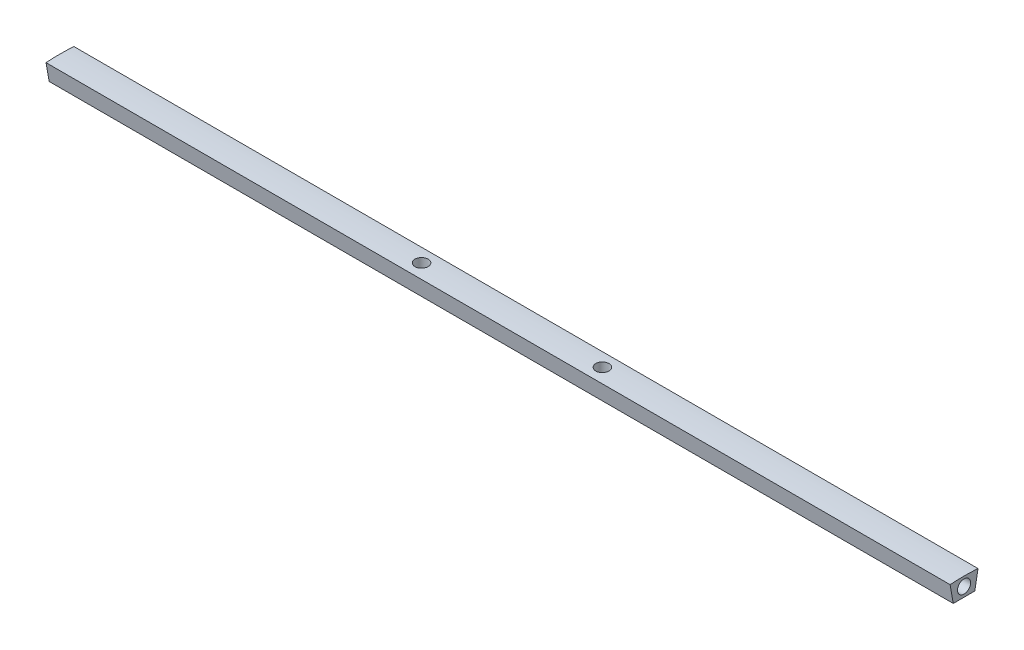
SolidWorks part; units mm, degrees
ref_plane "Спереди" through (0, 0, 0) normal (0, 0, 1) x (1, 0, 0)
ref_plane "Сверху" through (0, 0, 0) normal (0, 1, 0) x (1, 0, 0)
ref_plane "Справа" through (0, 0, 0) normal (1, 0, 0) x (0, 0, -1)
sketch "Эскиз1" plane through (0, 0, 0) normal (1, 0, 0) x (0, 0, -1)
  line L0 (-3.0855, 17.4987) -> (-2.3866, 13.535)
  line L1 (0, -1000) -> (0, 49000) construction
  line L2 (2.3866, 13.535) -> (3.0855, 17.4987)
  line L3 (-2.3866, 13.535) -> (2.3866, 13.535)
  arc A0 (-35.7, 0) -> (35.7, 0) centre (0, -27.3954) cw construction
  arc A1 (-30.5039, 0) -> (30.5039, 0) centre (0, -27.3954) cw construction
  arc A2 (-3.0855, 17.4987) -> (3.0855, 17.4987) centre (0, -27.3954) cw
  dimension "D1" = 45
  dimension "D2" = 4
  dimension "D3" = 71.4
  dimension "D4" = 10
extrude "Бобышка-Вытянуть1" add sketch "Эскиз1" along normal mid plane 200
sketch "Эскиз2" plane through (100, 0, 0) normal (1, 0, 0) x (0, 0, -1)
  circle A0 centre (0, 15.6046) radius 1.45
  arc A1 (3.0855, 17.4987) -> (-3.0855, 17.4987) centre (0, -27.3954) ccw construction
  arc A2 (3.0855, 17.4987) -> (-3.0855, 17.4987) centre (0, -27.3954) ccw construction
  circle A3 centre (0, -27.3954) radius 43 construction
  dimension "D1" = 86
  dimension "D2" = 2.9
extrude "Вырез-Вытянуть1" cut sketch "Эскиз2" against normal blind 10
mirror "Зеркальное отражение1" about plane through (0, 0, 0) normal (1, 0, 0) of "Вырез-Вытянуть1"
sketch "Эскиз3" plane through (0, 13.535, 0) normal (0, -1, 0) x (1, 0, 0)
  line L0 (0, -1000) -> (0, 49000) construction
  line L1 (-1000, 0) -> (49000, 0) construction
  circle A0 centre (-20, 0) radius 1.45
  circle A1 centre (20, 0) radius 1.45
  dimension "D2" = 2.9
  dimension "D1" = 20
extrude "Вырез-Вытянуть2" cut sketch "Эскиз3" against normal blind 10
